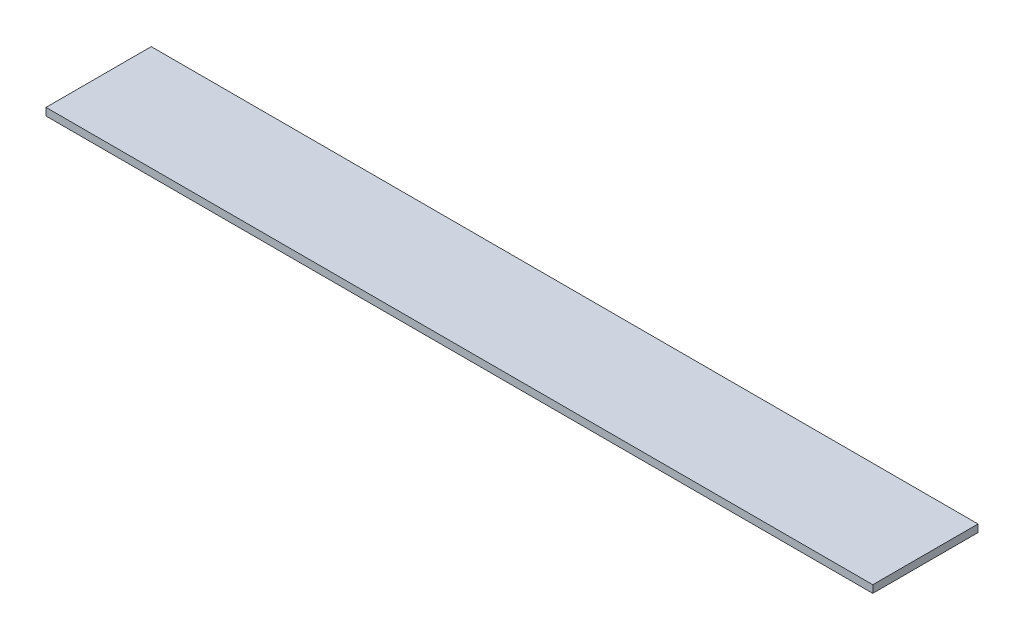
SolidWorks part; units mm, degrees
ref_plane "Front Plane" through (0, 0, 0) normal (0, 0, 1) x (1, 0, 0)
ref_plane "Top Plane" through (0, 0, 0) normal (0, 1, 0) x (1, 0, 0)
ref_plane "Right Plane" through (0, 0, 0) normal (1, 0, 0) x (0, 0, -1)
sketch "Sketch1" plane through (0, 0, 0) normal (0, 1, 0) x (1, 0, 0)
  line L1 (698.5, 88.9) -> (-698.5, 88.9)
  line L2 (698.5, 88.9) -> (698.5, -88.9)
  line L3 (698.5, -88.9) -> (-698.5, -88.9)
  line L4 (-698.5, 88.9) -> (-698.5, -88.9)
  line L5 (698.5, 88.9) -> (-698.5, -88.9) construction
  line L6 (698.5, -88.9) -> (-698.5, 88.9) construction
  point P0 (0, 0)
  dimension "D1" = 177.8
  dimension "D2" = 1397
extrude "Boss-Extrude1" add sketch "Sketch1" along normal blind 12.7 contours L1 L4 L3 L2
